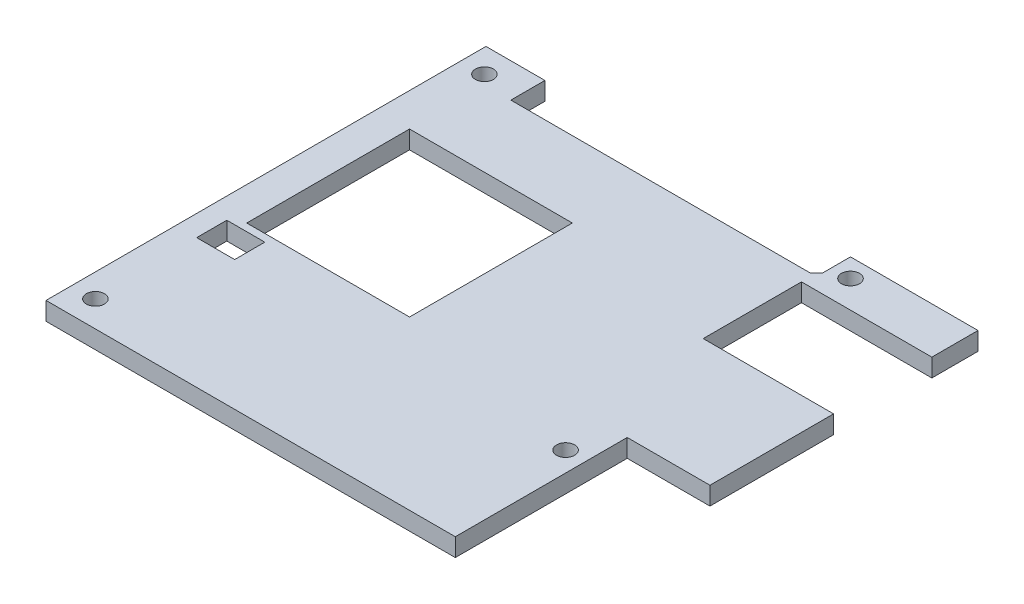
SolidWorks part; units mm, degrees
ref_plane "前视基准面" through (0, 0, 0) normal (0, 0, 1) x (1, 0, 0)
ref_plane "上视基准面" through (0, 0, 0) normal (0, 1, 0) x (1, 0, 0)
ref_plane "右视基准面" through (0, 0, 0) normal (1, 0, 0) x (0, 0, -1)
sketch "草图1" plane through (0, 0, 0) normal (0, 1, 0) x (1, 0, 0)
  line L0 (1.7, 15.1419) -> (1.7, 13.9998) construction
  line L1 (-7.176, -16.51) -> (74.421, -16.51)
  line L2 (-7.176, -16.51) -> (-7.176, 56.452)
  line L3 (-7.176, 56.452) -> (74.421, 56.452)
  line L4 (74.421, -16.51) -> (74.421, 56.452)
  line L5 (2.6, 50.8) -> (53.276, 50.8)
  line L6 (2.6, 50.8) -> (2.6, 56.452)
  line L7 (2.6, 56.452) -> (53.276, 56.452)
  line L8 (53.276, 50.8) -> (53.276, 56.452)
  line L9 (1.2985, 14.6) -> (2.0408, 14.6) construction
  line L11 (-1.65, 11.25) -> (25.35, 11.25)
  line L12 (-1.65, 11.25) -> (-1.65, 38.25)
  line L13 (-1.65, 38.25) -> (25.35, 38.25)
  line L14 (25.35, 11.25) -> (25.35, 38.25)
  line L15 (-3.7, 10) -> (2.6, 10)
  line L16 (-3.7, 10) -> (-3.7, 5)
  line L17 (-3.7, 5) -> (2.6, 5)
  line L18 (2.6, 10) -> (2.6, 5)
  line L19 (74.421, 48.8) -> (52.8, 48.8)
  line L20 (74.421, 48.8) -> (74.421, 32.5)
  line L21 (74.421, 32.5) -> (52.8, 32.5)
  line L22 (52.8, 48.8) -> (52.8, 32.5)
  line L23 (74.421, 12) -> (60.7, 12)
  line L24 (74.421, 12) -> (74.421, -16.51)
  line L25 (74.421, -16.51) -> (60.7, -16.51)
  line L26 (60.7, 12) -> (60.7, -16.51)
  circle A0 centre (-3.302, -12.192) radius 1.5
  circle A1 centre (-3.302, 52.324) radius 1.5
  circle A2 centre (56.388, 53.34) radius 1.5
  circle A3 centre (57.404, 5.08) radius 1.5
  dimension "D13" = 3
  dimension "D14" = 3
  dimension "D15" = 3
  dimension "D16" = 3
  dimension "D1" = 72.962
  dimension "D2" = 81.597
  dimension "D3" = 7.176
  dimension "D4" = 16.51
  dimension "D5" = 3.302
  dimension "D6" = 12.192
  dimension "D7" = 3.302
  dimension "D8" = 52.324
  dimension "D9" = 57.404
  dimension "D10" = 5.08
  dimension "D11" = 53.34
  dimension "D12" = 56.388
  dimension "D17" = 2.6
  dimension "D18" = 53.276
  dimension "D19" = 50.8
  dimension "D20" = 1.7
  dimension "D21" = 14.6
  dimension "D22" = 3.35
  dimension "D23" = 3.35
  dimension "D24" = 27
  dimension "D25" = 27
  dimension "D26" = 3.7
  dimension "D27" = 5
  dimension "D28" = 2.6
  dimension "D29" = 10
  dimension "D30" = 52.8
  dimension "D31" = 32.5
  dimension "D32" = 48.8
  dimension "D33" = 60.7
  dimension "D35" = 12
extrude "凸台-拉伸1" add sketch "草图1" along normal blind 3 contours L26 L23 L4 L21 L22 L19 L3 L8 L5 L6 L2 L1 A3 A2 A1 A0 L14 L11 L12 L13 L15 L18 L17 L16
chamfer "倒角1" distance 1 angle 45 1 edges at (53.276, 1.5, -50.8)
